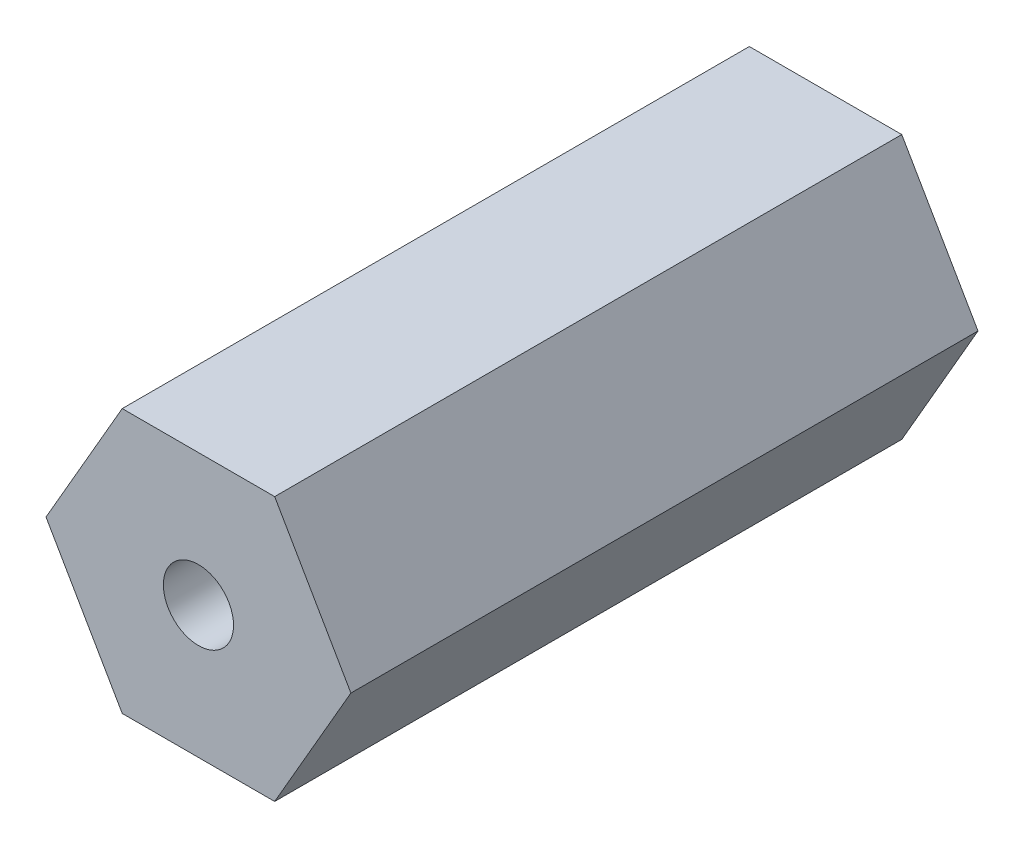
SolidWorks part; units mm, degrees
ref_plane "Front Plane" through (0, 0, 0) normal (0, 0, 1) x (1, 0, 0)
ref_plane "Top Plane" through (0, 0, 0) normal (0, 1, 0) x (1, 0, 0)
ref_plane "Right Plane" through (0, 0, 0) normal (1, 0, 0) x (0, 0, -1)
sketch "Sketch1" plane through (0, 0, 0) normal (0, 0, 1) x (1, 0, 0)
  line L1 (-5.8659, 0) -> (-2.9329, -5.08)
  line L2 (-2.9329, -5.08) -> (2.9329, -5.08)
  line L3 (2.9329, -5.08) -> (5.8659, 0)
  line L4 (5.8659, 0) -> (2.9329, 5.08)
  line L5 (2.9329, 5.08) -> (-2.9329, 5.08)
  line L6 (-2.9329, 5.08) -> (-5.8659, 0)
  circle A0 centre (0, 0) radius 5.08 construction
  circle A1 centre (0, 0) radius 5.08
  dimension "D2" = 10.16
extrude "Boss-Extrude1" add sketch "Sketch1" along normal blind 24.13 contours A1 | A1 L5 L6 | A1 L4 L5 | A1 L3 L4 | A1 L2 L3 | A1 L6 L1 | A1 L1 L2
hole_wizard "M3x0.5 Tapped Hole1" positions "Sketch2" profile "Sketch3" tap size "M3x0.5" standard "ANSI Metric" end condition through all
sketch "Sketch2" plane through (0, 0, 24.13) normal (0, 0, 1) x (1, 0, 0)
  point P0 (0, 0)
sketch "Sketch3" plane through (0, 0, 24.13) normal (1, 0, 0) x (0, -1, 0)
  line L0 (0, 0) -> (0, 24.13)
  line L1 (0, 24.13) -> (1.35, 24.13)
  line L2 (1.35, 24.13) -> (1.35, 0)
  line L5 (1.35, 0) -> (0, 0)
  line L11 (0, -6.35) -> (0, 107.95) construction
  dimension "Thread Major Dia." = 2.7
  dimension "Thru Tap Drill Depth" = 24.13
